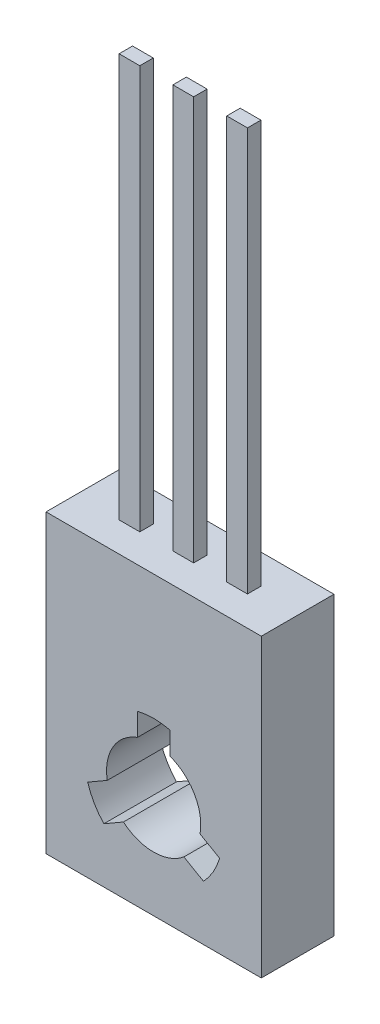
SolidWorks part; units mm, degrees
ref_plane "Front Plane" through (0, 0, 0) normal (0, 0, 1) x (1, 0, 0)
ref_plane "Top Plane" through (0, 0, 0) normal (0, 1, 0) x (1, 0, 0)
ref_plane "Right Plane" through (0, 0, 0) normal (1, 0, 0) x (0, 0, -1)
sketch "Sketch1" plane through (0, 0, 0) normal (0, 0, 1) x (1, 0, 0)
  line L1 (-4, 5.5) -> (4, 5.5)
  line L2 (-4, 5.5) -> (-4, -5.5)
  line L3 (-4, -5.5) -> (4, -5.5)
  line L4 (4, 5.5) -> (4, -5.5)
  line L5 (-4, 5.5) -> (4, -5.5) construction
  line L6 (-4, -5.5) -> (4, 5.5) construction
  circle A0 centre (0, -1.7) radius 2.555
  point P0 (0, 0)
  dimension "D3" = 5.11
  dimension "D1" = 11
  dimension "D2" = 8
  dimension "D4" = 3.8
extrude "Boss-Extrude1" add sketch "Sketch1" along normal mid plane 2.7
sketch "Sketch2" plane through (0, 5.5, 0) normal (0, 1, 0) x (1, 0, 0)
  line L0 (0, 0.8819) -> (0, -0.7814) construction
  line L1 (-0.385, 0.25) -> (0.385, 0.25)
  line L2 (-0.385, 0.25) -> (-0.385, -0.25)
  line L3 (-0.385, -0.25) -> (0.385, -0.25)
  line L4 (0.385, 0.25) -> (0.385, -0.25)
  line L5 (-0.385, 0.25) -> (0.385, -0.25) construction
  line L6 (-0.385, -0.25) -> (0.385, 0.25) construction
  line L7 (-2.385, 0.25) -> (-1.615, 0.25)
  line L8 (-2.385, 0.25) -> (-2.385, -0.25)
  line L9 (-2.385, -0.25) -> (-1.615, -0.25)
  line L10 (-1.615, 0.25) -> (-1.615, -0.25)
  line L11 (-2.385, 0.25) -> (-1.615, -0.25) construction
  line L12 (-2.385, -0.25) -> (-1.615, 0.25) construction
  line L13 (2.385, -0.25) -> (1.615, -0.25)
  line L14 (1.615, 0.25) -> (1.615, -0.25)
  line L15 (2.385, 0.25) -> (1.615, 0.25)
  line L16 (2.385, 0.25) -> (2.385, -0.25)
  point P0 (0, 0)
  point P7 (-2, 0)
  dimension "D1" = 0.5
  dimension "D2" = 0.77
  dimension "D3" = 0.77
  dimension "D4" = 0.5
  dimension "D5" = 2
extrude "Boss-Extrude2" add sketch "Sketch2" along normal blind 15
sketch "Sketch4" plane through (0, 0, 1.35) normal (0, 0, 1) x (1, 0, 0)
  line L0 (0, 0.8936) -> (0, -1.7) construction
  line L3 (-0.6, 0.8232) -> (-0.6, -0.0561)
  line L4 (0.6, 0.8232) -> (0.6, -0.0561)
  line L5 (2.4852, -2.442) -> (1.7237, -2.0023)
  line L6 (1.8852, -3.4812) -> (1.1237, -3.0416)
  line L7 (-1.8852, -3.4812) -> (-1.1237, -3.0416)
  line L8 (-2.4852, -2.442) -> (-1.7237, -2.0023)
  arc A0 (-1.1237, -3.0416) -> (1.1237, -3.0416) centre (0, -1.7) ccw
  arc A1 (-1.8852, -3.4812) -> (1.8852, -3.4812) centre (0, -1.7) ccw
  arc A2 (-0.6, -0.0561) -> (-1.7237, -2.0023) centre (0, -1.7) ccw
  arc A3 (-0.6, 0.8232) -> (-2.4852, -2.442) centre (0, -1.7) ccw
  arc A4 (1.7237, -2.0023) -> (0.6, -0.0561) centre (0, -1.7) ccw
  arc A5 (2.4852, -2.442) -> (0.6, 0.8232) centre (0, -1.7) ccw
  point P22 (0, -1.7)
  dimension "D1" = 3.5
  dimension "D2" = 0.6
  dimension "D3" = 3
extrude "Boss-Extrude3" add sketch "Sketch4" against normal up to surface (2.7 mm away) up to face at (0, 0, -1.35)
